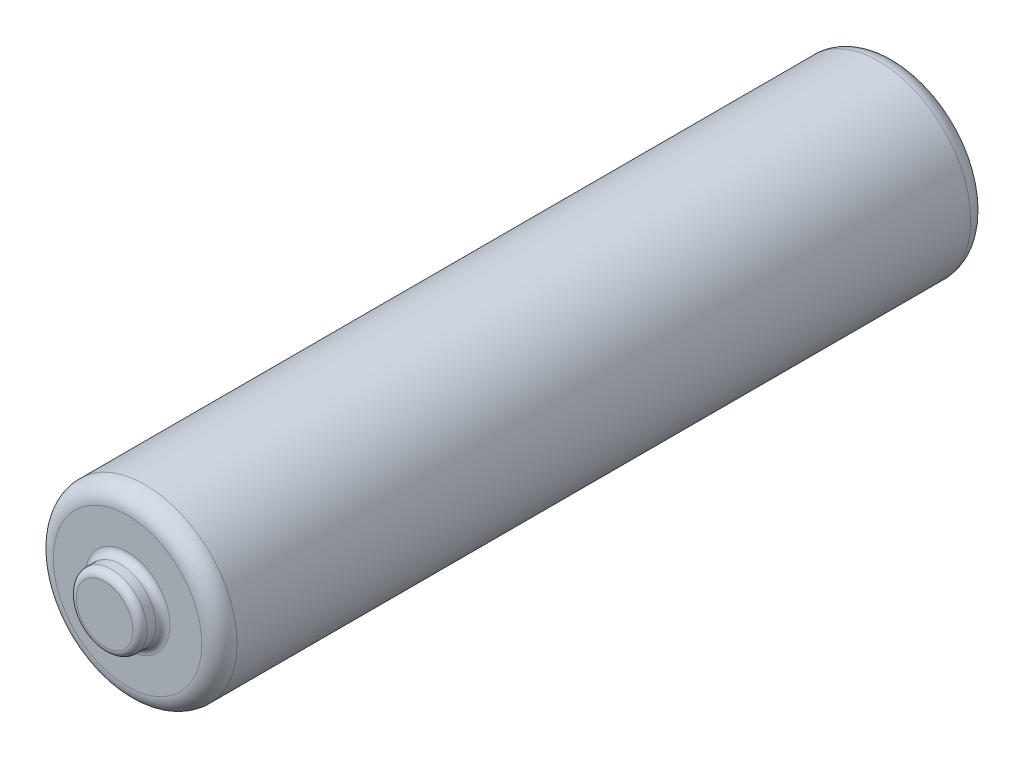
SolidWorks part; units mm, degrees
ref_plane "Front Plane" through (0, 0, 0) normal (0, 0, 1) x (1, 0, 0)
ref_plane "Top Plane" through (0, 0, 0) normal (0, 1, 0) x (1, 0, 0)
ref_plane "Right Plane" through (0, 0, 0) normal (1, 0, 0) x (0, 0, -1)
sketch "Sketch1" plane through (0, 0, 0) normal (0, 0, 1) x (1, 0, 0)
  circle A0 centre (0, 0) radius 5.2
  dimension "D1" = 10.4
extrude "Boss-Extrude1" add sketch "Sketch1" along normal blind 43.5
sketch "Sketch2" plane through (0, 0, 43.5) normal (0, 0, 1) x (1, 0, 0)
  circle A0 centre (0, 0) radius 2
  dimension "D1" = 4
extrude "Boss-Extrude2" add sketch "Sketch2" along normal blind 1.3
fillet "Fillet1" radius 1 2 edges at (5.2, 0, 0) (5.2, 0, 43.5)
fillet "Fillet2" radius 0.4 2 edges at (2, 0, 44.8) (2, 0, 43.5)
